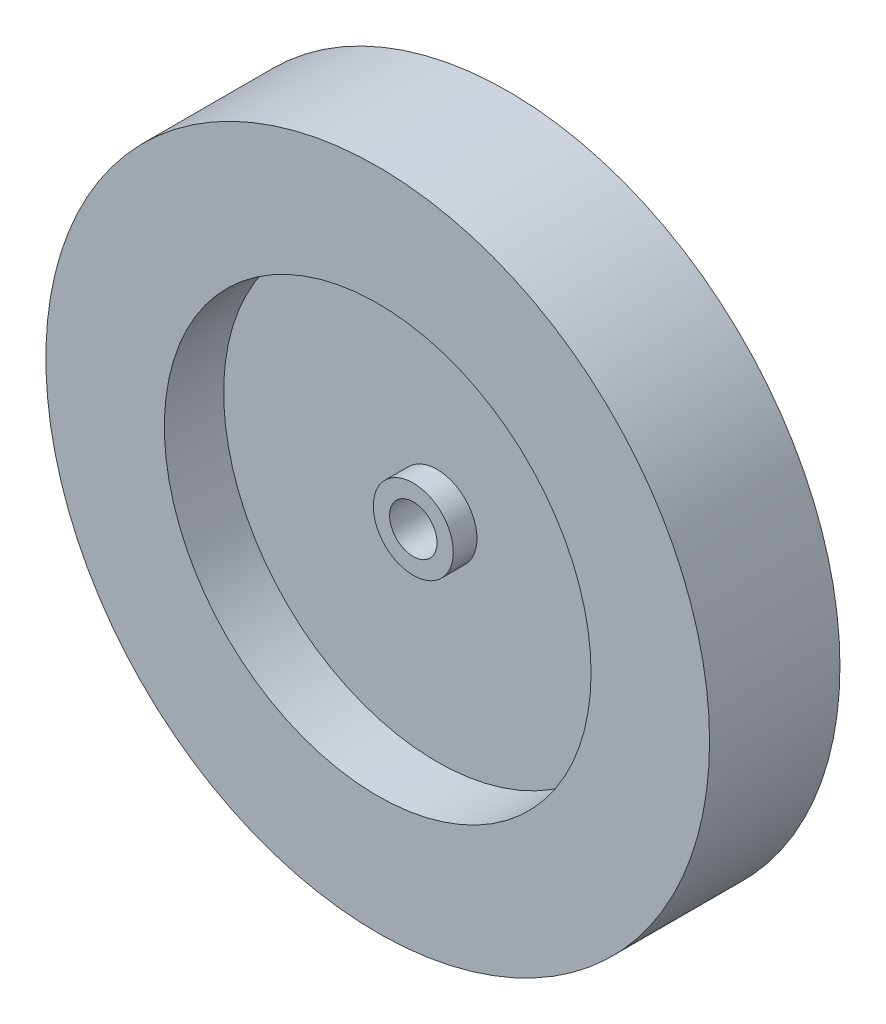
SolidWorks part; units mm, degrees
material "ABS"
ref_plane "Front Plane" through (0, 0, 0) normal (0, 0, 1) x (1, 0, 0)
ref_plane "Top Plane" through (0, 0, 0) normal (0, 1, 0) x (1, 0, 0)
ref_plane "Right Plane" through (0, 0, 0) normal (1, 0, 0) x (0, 0, -1)
sketch "Sketch1" plane through (0, 0, 0) normal (0, 0, 1) x (1, 0, 0)
  circle A0 centre (0, 0) radius 88.9
  circle A1 centre (0, 0) radius 69.85
extrude "Boss-Extrude1" add sketch "Sketch1" along normal mid plane 34.925
sketch "Sketch2" plane through (0, 0, 0) normal (0, 0, 1) x (1, 0, 0)
  circle A0 centre (0, 0) radius 69.85
extrude "Boss-Extrude2" add sketch "Sketch2" along normal mid plane 3.175
sketch "Sketch3" plane through (0, 0, 0) normal (0, 0, 1) x (1, 0, 0)
  circle A0 centre (0, 0) radius 69.85
  circle A1 centre (0, 0) radius 57.15
extrude "Boss-Extrude3" add sketch "Sketch3" along normal mid plane 34.925 separate body
sketch "Sketch4" plane through (0, 0, 0) normal (0, 0, 1) x (1, 0, 0)
  circle A0 centre (0, 0) radius 10.7156
extrude "Boss-Extrude4" add sketch "Sketch4" along normal blind 7.9375
sketch "Sketch5" plane through (0, 0, 0) normal (0, 0, 1) x (1, 0, 0)
  circle A0 centre (0, 0) radius 9.525
extrude "Boss-Extrude5" add sketch "Sketch5" against normal blind 25.4
sketch "Sketch6" plane through (0, 0, 0) normal (0, 0, 1) x (1, 0, 0)
  circle A0 centre (0, 0) radius 6.35
extrude "Cut-Extrude1" cut sketch "Sketch6" against normal through all both and the other way through all
